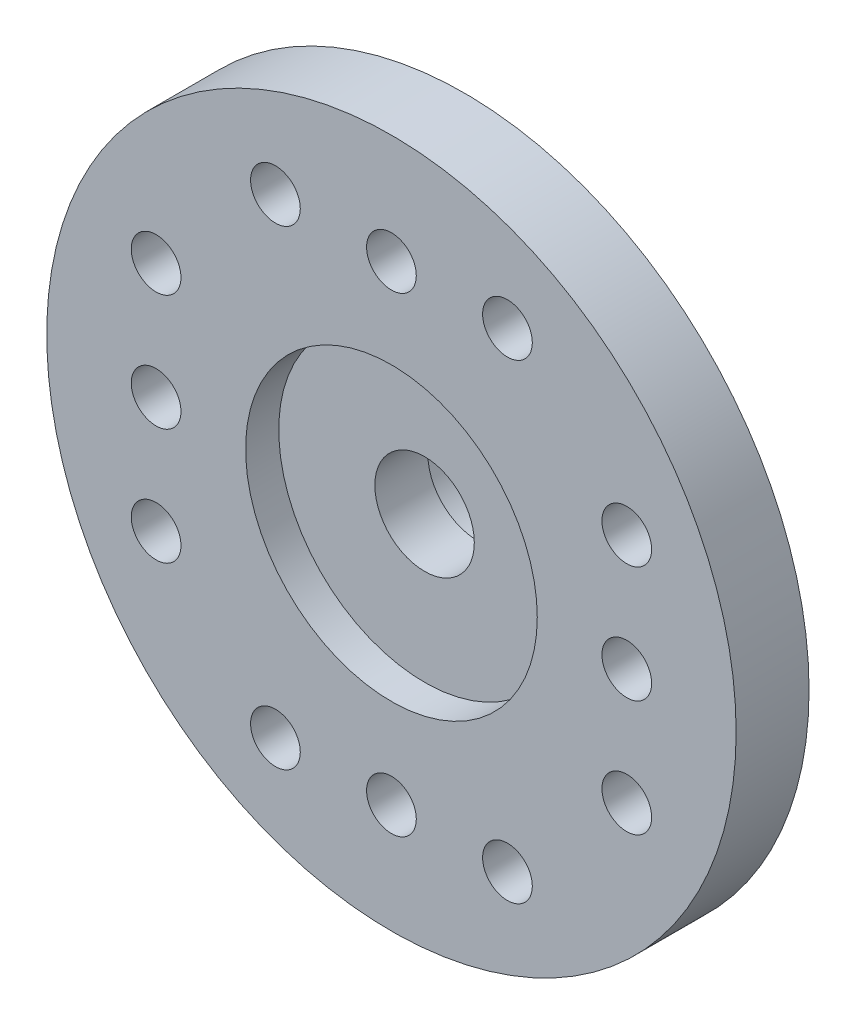
SolidWorks part; units mm, degrees
ref_plane "前视基准面" through (0, 0, 0) normal (0, 0, 1) x (1, 0, 0)
ref_plane "上视基准面" through (0, 0, 0) normal (0, 1, 0) x (1, 0, 0)
ref_plane "右视基准面" through (0, 0, 0) normal (1, 0, 0) x (0, 0, -1)
other "Configuration Table"
sketch "草图1" plane through (0, 0, 0) normal (0, 0, 1) x (1, 0, 0)
  circle A1 centre (0, 0) radius 10.4
  dimension "D2" = 20.8
extrude "凸台-拉伸1" add sketch "草图1" along normal blind 2.2
sketch "草图2" plane through (0, 0, 0) normal (0, 0, -1) x (-1, 0, 0)
  circle A0 centre (0, 0) radius 4.35
  dimension "D1" = 8.7
extrude "凸台-拉伸2" add sketch "草图2" along normal blind 3.3
sketch "草图3" plane through (0, 0, 0) normal (0, 0, -1) x (-1, 0, 0)
  circle A0 centre (0, 0) radius 1.5
  dimension "D1" = 3
extrude "切除-拉伸1" cut sketch "草图3" against normal through all from surface at 3.3 starting at face at (-4.35, 0, -3.3)
sketch "草图4" plane through (0, 0, 2.2) normal (0, 0, 1) x (1, 0, 0)
  circle A0 centre (0, 0) radius 4.4
  dimension "D1" = 8.8
extrude "切除-拉伸2" cut sketch "草图4" against normal blind 1
sketch "草图5" plane through (0, 0, 2.2) normal (0, 0, 1) x (1, 0, 0)
  line L0 (-7.1, 7.1) -> (-7.1, -7.1) construction
  line L1 (-7.1, 7.1) -> (7.1, 7.1) construction
  line L2 (-7.1, -7.1) -> (7.1, -7.1) construction
  line L3 (7.1, 7.1) -> (7.1, -7.1) construction
  line L4 (-7.1, 7.1) -> (7.1, -7.1) construction
  line L5 (-7.1, -7.1) -> (7.1, 7.1) construction
  line L6 (0, 0) -> (0, 7.1) construction
  circle A0 centre (0, 7.1) radius 0.75
  circle A1 centre (3.5, 7.1) radius 0.75
  circle A2 centre (-3.5, 7.1) radius 0.75
  circle A3 centre (7.1, 3.5) radius 0.75
  circle A4 centre (7.1, 0) radius 0.75
  circle A5 centre (7.1, -3.5) radius 0.75
  circle A6 centre (3.5, -7.1) radius 0.75
  circle A7 centre (0, -7.1) radius 0.75
  circle A8 centre (-3.5, -7.1) radius 0.75
  circle A9 centre (-7.1, -3.5) radius 0.75
  circle A10 centre (-7.1, 0) radius 0.75
  circle A11 centre (-7.1, 3.5) radius 0.75
  point P1 (0, 0)
  point P35 (0, 0)
  dimension "D2" = 1.5
  dimension "D3" = 7
  dimension "D1" = 14.2
  dimension "D4" = 4
extrude "切除-拉伸3" cut sketch "草图5" against normal through all
sketch "草图6" plane through (0, 0, -3.3) normal (0, 0, -1) x (-1, 0, 0)
  circle A0 centre (0, 0) radius 2
  dimension "D1" = 4
extrude "切除-拉伸4" cut sketch "草图6" against normal blind 2.9
